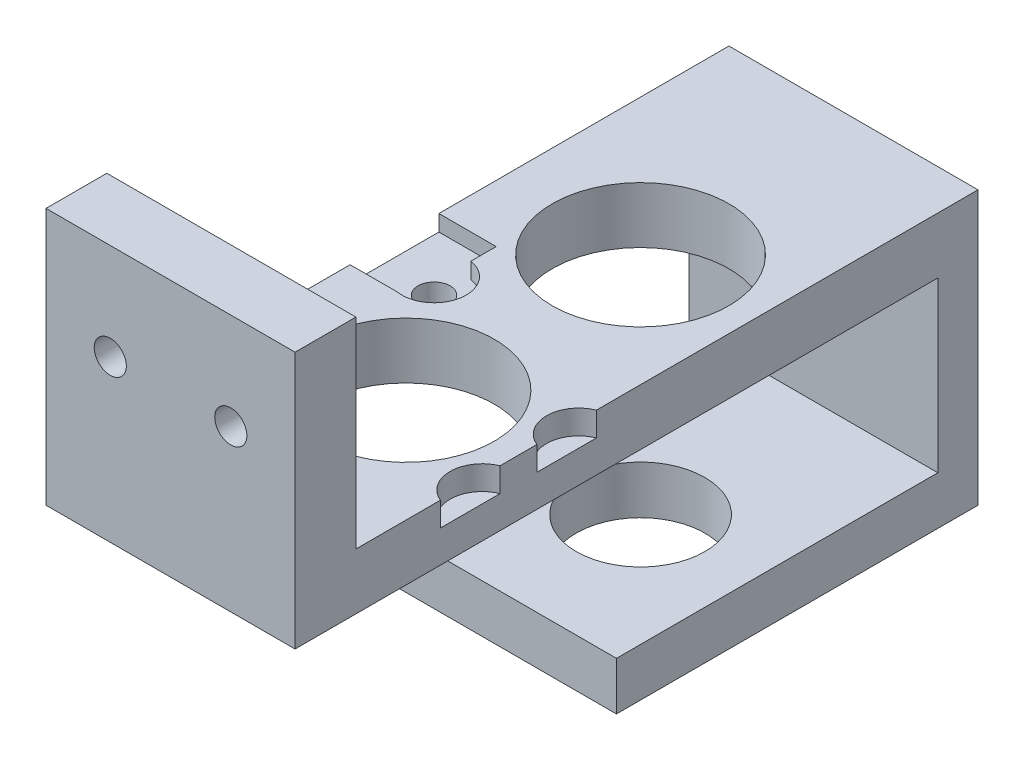
SolidWorks part; units mm, degrees
material "ABS"
ref_plane "Front Plane" through (0, 0, 0) normal (0, 0, 1) x (1, 0, 0)
ref_plane "Top Plane" through (0, 0, 0) normal (0, 1, 0) x (1, 0, 0)
ref_plane "Right Plane" through (0, 0, 0) normal (1, 0, 0) x (0, 0, -1)
sketch "Sketch1" plane through (0, 0, 0) normal (0, 1, 0) x (1, 0, 0)
  line L1 (-50.1619, 28.7652) -> (-19.1619, 28.7652)
  line L2 (-50.1619, 28.7652) -> (-50.1619, -56.2348)
  line L3 (-50.1619, -56.2348) -> (-19.1619, -56.2348)
  line L4 (-19.1619, 28.7652) -> (-19.1619, -56.2348)
  dimension "D1" = 85
  dimension "D2" = 31
extrude "Boss-Extrude1" add sketch "Sketch1" along normal blind 7
sketch "Sketch2" plane through (0, 7, 0) normal (0, 1, 0) x (1, 0, 0)
  line L0 (-50.1619, -56.2348) -> (-19.1619, -56.2348) construction
  line L1 (-50.1619, 28.7652) -> (-50.1619, -56.2348) construction
  circle A0 centre (-33.1619, 0.7652) radius 11
  dimension "D1" = 22
  dimension "D2" = 57
  dimension "D3" = 17
extrude "Cut-Extrude1" cut sketch "Sketch2" against normal blind 100
sketch "Sketch3" plane through (0, 7, 0) normal (0, 1, 0) x (1, 0, 0)
  line L0 (-50.1619, 28.7652) -> (-50.1619, -56.2348) construction
  circle A0 centre (-33.1619, -28.4348) radius 11
  circle A1 centre (-33.1619, 0.7652) radius 11 construction
  dimension "D1" = 22
  dimension "D2" = 29.2
  dimension "D3" = 17
extrude "Cut-Extrude2" cut sketch "Sketch3" against normal blind 7
sketch "Sketch4" plane through (0, 7, 0) normal (0, 1, 0) x (1, 0, 0)
  line L0 (-19.1619, -56.2348) -> (-19.1619, 28.7652) construction
  line L1 (-50.1619, -56.2348) -> (-19.1619, -56.2348)
  line L2 (-50.1619, -56.2348) -> (-50.1619, -48.6648)
  line L3 (-50.1619, -48.6648) -> (-19.1619, -48.6648)
  line L4 (-19.1619, -56.2348) -> (-19.1619, -48.6648)
  dimension "D1" = 7.57
extrude "Boss-Extrude3" add sketch "Sketch4" along normal blind 25
sketch "Sketch5" plane through (0, 0, 48.6648) normal (0, 0, -1) x (-1, 0, 0)
  line L0 (50.1619, 32) -> (50.1619, 7) construction
  line L1 (19.1619, 32) -> (50.1619, 32) construction
  circle A0 centre (42.1619, 20) radius 2
  circle A1 centre (27.1619, 20) radius 2
  dimension "D1" = 4
  dimension "D2" = 4
  dimension "D3" = 8
  dimension "D4" = 15
  dimension "D5" = 0
  dimension "D6" = 12
extrude "Cut-Extrude3" cut sketch "Sketch5" against normal blind 14
sketch "Sketch6" plane through (0, 7, 0) normal (0, 1, 0) x (1, 0, 0)
  circle A0 centre (-43.6619, -14.4348) radius 2
  circle A1 centre (-43.6619, -42.4348) radius 2
  circle A2 centre (-33.1619, -28.4348) radius 11 construction
  dimension "D1" = 4
  dimension "D2" = 4
  dimension "D3" = 28
  dimension "D4" = 10.5
  dimension "D5" = 14
  dimension "D6" = 0
extrude "Cut-Extrude4" cut sketch "Sketch6" against normal blind 14
sketch "Sketch9" plane through (0, 7, 0) normal (0, 1, 0) x (1, 0, 0)
  circle A2 centre (-33.1619, 0.7652) radius 8
  circle A3 centre (-33.1619, 0.7652) radius 11 construction
  dimension "D1" = 16
  dimension "D2" = 0
sketch "Sketch10" plane through (0, 0, 0) normal (0, -1, 0) x (1, 0, 0)
  line L0 (-19.1619, 56.2348) -> (-19.1619, -28.7652) construction
  line L1 (-50.1619, -28.7652) -> (-19.1619, -28.7652)
  line L2 (-50.1619, -28.7652) -> (-50.1619, -23.7652)
  line L3 (-50.1619, -23.7652) -> (-19.1619, -23.7652)
  line L4 (-19.1619, -28.7652) -> (-19.1619, -23.7652)
  dimension "D1" = 5
extrude "Boss-Extrude4" add sketch "Sketch10" along normal blind 27
sketch "Sketch11" plane through (0, 0, -23.7652) normal (0, 0, 1) x (1, 0, 0)
  line L0 (-19.1619, -27) -> (-19.1619, 0) construction
  line L1 (-50.1619, -27) -> (-19.1619, -27)
  line L2 (-50.1619, -27) -> (-50.1619, -21)
  line L3 (-50.1619, -21) -> (-19.1619, -21)
  line L4 (-19.1619, -27) -> (-19.1619, -21)
  dimension "D1" = 6
extrude "Boss-Extrude5" add sketch "Sketch11" along normal blind 40
extrude "Cut-Extrude5" cut sketch "Sketch9" against normal blind 40
sketch "Sketch13" plane through (0, 7, 0) normal (0, 1, 0) x (1, 0, 0)
  circle A0 centre (-43.6619, -14.4348) radius 4
  circle A2 centre (-43.6619, -14.4348) radius 2 construction
  circle A3 centre (-43.6619, -42.4348) radius 4
  circle A4 centre (-43.6619, -42.4348) radius 2 construction
  circle A5 centre (-43.6619, -42.4348) radius 2 construction
  dimension "D1" = 0
  dimension "D2" = 8
  dimension "D3" = 0
  dimension "D4" = 0
  dimension "D5" = 8
extrude "Cut-Extrude6" cut sketch "Sketch13" against normal blind 2
sketch "Sketch15" plane through (0, 7, 0) normal (0, 1, 0) x (1, 0, 0)
  line L0 (-50.1619, 28.7652) -> (-50.1619, -48.6648) construction
  line L3 (-50.1619, -7.3373) -> (-43.0297, -7.3373)
  line L6 (-50.1619, -7.3373) -> (-50.1619, -18.3845)
  line L7 (-50.1619, -18.3845) -> (-43.0297, -18.3845)
  line L8 (-43.0297, -7.3373) -> (-43.0297, -18.3845)
  line L9 (-19.1619, -48.6648) -> (-50.1619, -48.6648) construction
  line L10 (-50.1619, -39.308) -> (-42.4267, -39.308)
  line L11 (-50.1619, -39.308) -> (-50.1619, -48.6648)
  line L12 (-50.1619, -48.6648) -> (-42.4267, -48.6648)
  line L13 (-42.4267, -39.308) -> (-42.4267, -48.6648)
  circle A4 centre (-43.6619, -14.4348) radius 4 construction
extrude "Cut-Extrude9" cut sketch "Sketch15" against normal blind 2
sketch "Sketch17" plane through (0, 7, 0) normal (0, 1, 0) x (1, 0, 0)
  line L0 (-17.6619, -22.4348) -> (-17.6619, -34.4348)
  line L1 (-17.6619, -28.4348) -> (-10.263, -28.4348)
  circle A0 centre (-17.6619, -22.4348) radius 4
  circle A1 centre (-17.6619, -34.4348) radius 4
  point P6 (0, 0)
  point P8 (-33.1619, -28.4348)
  line M12 (-19.1619, -48.6648) -> (-19.1619, 28.7652)
  dimension "D1" = 8
  dimension "D2" = 8
  dimension "D3" = 12
  dimension "D4" = 0
  dimension "D5" = 15.5
extrude "Cut-Extrude10" cut sketch "Sketch17" against normal blind 3 contours A0 M12 | A1 M12
